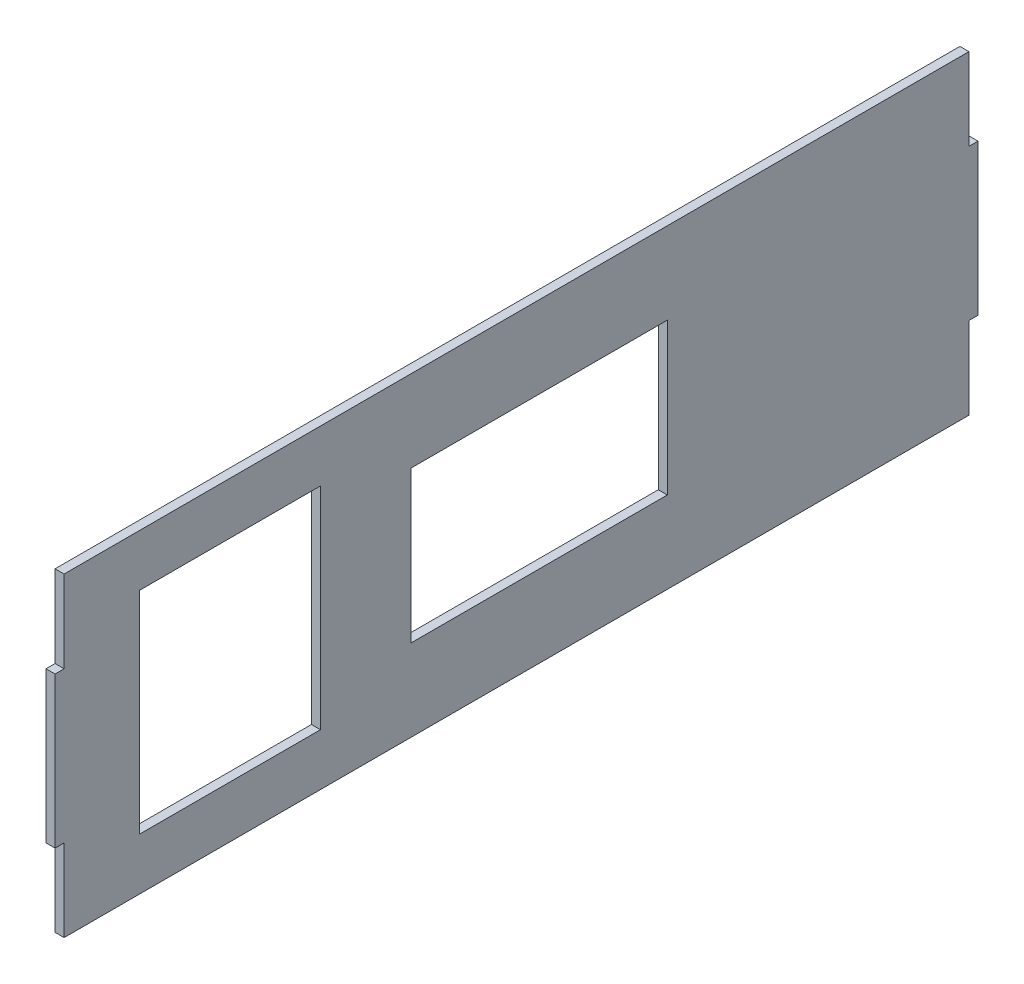
SolidWorks part; units mm, degrees
ref_plane "Front Plane" through (0, 0, 0) normal (0, 0, 1) x (1, 0, 0)
ref_plane "Top Plane" through (0, 0, 0) normal (0, 1, 0) x (1, 0, 0)
ref_plane "Right Plane" through (0, 0, 0) normal (1, 0, 0) x (0, 0, -1)
sketch "Sketch1" plane through (0, 0, 0) normal (1, 0, 0) x (0, 0, -1)
  line L0 (-174.3547, 63.0717) -> (125.6453, 63.0717)
  line L1 (125.6453, 63.0717) -> (125.6453, 35.8717)
  line L2 (125.6453, 35.8717) -> (128.6453, 35.8717)
  line L3 (128.6453, 35.8717) -> (128.6453, -14.1283)
  line L4 (128.6453, -14.1283) -> (125.6453, -14.1283)
  line L5 (125.6453, -14.1283) -> (125.6453, -41.3283)
  line L6 (125.6453, -41.3283) -> (-174.3547, -41.3283)
  line L7 (-174.3547, -41.3283) -> (-174.3547, -14.1283)
  line L8 (-174.3547, -14.1283) -> (-177.3547, -14.1283)
  line L9 (-177.3547, -14.1283) -> (-177.3547, 35.8717)
  line L10 (-177.3547, 35.8717) -> (-174.3547, 35.8717)
  line L11 (-174.3547, 35.8717) -> (-174.3547, 63.0717)
  dimension "D1" = 300
  dimension "D2" = 50
  dimension "D3" = 50
  dimension "D4" = 27.2
  dimension "D5" = 27.2
  dimension "D6" = 27.2
  dimension "D7" = 3
  dimension "D8" = 3
  dimension "D9" = 3
  dimension "D10" = 3
extrude "Boss-Extrude1" add sketch "Sketch1" along normal blind 3
sketch "Sketch2" plane through (3, 0, 0) normal (1, 0, 0) x (0, 0, -1)
  line L0 (125.6453, 63.0717) -> (-174.3547, 63.0717) construction
  line L1 (-149.3547, 45.8717) -> (-89.3547, 45.8717)
  line L2 (-149.3547, 45.8717) -> (-149.3547, -24.1283)
  line L3 (-149.3547, -24.1283) -> (-89.3547, -24.1283)
  line L4 (-89.3547, 45.8717) -> (-89.3547, -24.1283)
  line L6 (-174.3547, 63.0717) -> (-174.3547, 35.8717) construction
  dimension "D1" = 60
  dimension "D2" = 70
  dimension "D3" = 17.2
  dimension "D4" = 25
extrude "Cut-Extrude1" cut sketch "Sketch2" against normal blind 10
sketch "Sketch3" plane through (3, 0, 0) normal (1, 0, 0) x (0, 0, -1)
  line L0 (125.6453, 63.0717) -> (-174.3547, 63.0717) construction
  line L1 (-59.3547, 35.9717) -> (25.6453, 35.9717)
  line L2 (-59.3547, 35.9717) -> (-59.3547, -14.2283)
  line L3 (-59.3547, -14.2283) -> (25.6453, -14.2283)
  line L4 (25.6453, 35.9717) -> (25.6453, -14.2283)
  line L8 (-89.3547, 45.8717) -> (-89.3547, -24.1283) construction
  dimension "D1" = 85
  dimension "D2" = 50.2
  dimension "D3" = 27.1
  dimension "D4" = 30
extrude "Cut-Extrude2" cut sketch "Sketch3" against normal blind 10
